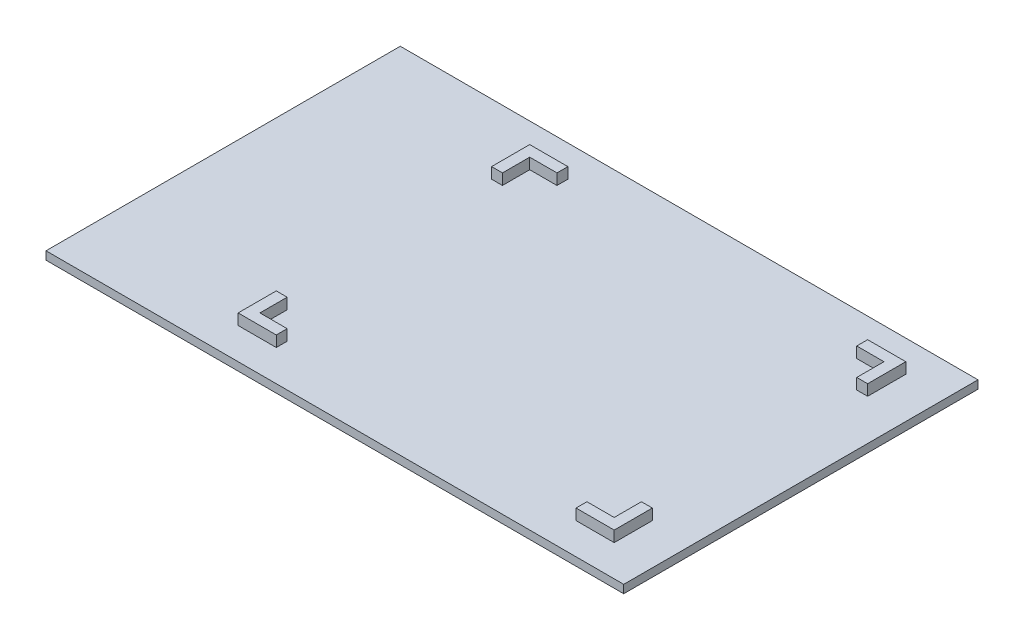
SolidWorks part; units mm, degrees
ref_plane "Front Plane" through (0, 0, 0) normal (0, 0, 1) x (1, 0, 0)
ref_plane "Top Plane" through (0, 0, 0) normal (0, 1, 0) x (1, 0, 0)
ref_plane "Right Plane" through (0, 0, 0) normal (1, 0, 0) x (0, 0, -1)
sketch "Sketch2" plane through (0, 0, 0) normal (0, 1, 0) x (1, 0, 0)
  line L0 (-106, 65) -> (-106, -65)
  line L1 (-106, -65) -> (106, -65)
  line L2 (106, -65) -> (106, 65)
  line L3 (106, 65) -> (-106, 65)
  point P2 (0, 65)
  point P5 (-106, 0)
  dimension "D1" = 212
  dimension "D2" = 130
extrude "Boss-Extrude1" add sketch "Sketch2" along normal blind 3
sketch "Sketch3" plane through (0, 3, 0) normal (0, 1, 0) x (1, 0, 0)
  line L0 (91, 53.5) -> (77, 53.5)
  line L1 (77, 53.5) -> (77, 49.5)
  line L2 (77, 49.5) -> (87, 49.5)
  line L3 (87, 49.5) -> (87, 39.5)
  line L4 (87, 39.5) -> (91, 39.5)
  line L5 (91, 39.5) -> (91, 53.5)
  line L6 (91, -39.5) -> (91, -53.5)
  line L7 (91, -53.5) -> (77, -53.5)
  line L8 (77, -53.5) -> (77, -49.5)
  line L9 (77, -49.5) -> (87, -49.5)
  line L10 (87, -49.5) -> (87, -39.5)
  line L11 (87, -39.5) -> (91, -39.5)
  line L12 (106, -65) -> (106, 65) construction
  line L13 (-106, -65) -> (106, -65) construction
  line L27 (22, 73.2387) -> (22, -80.6941) construction
  line L28 (-43, -49.5) -> (-43, -39.5)
  line L29 (-33, -49.5) -> (-43, -49.5)
  line L30 (-33, -53.5) -> (-33, -49.5)
  line L31 (-47, -53.5) -> (-33, -53.5)
  line L32 (-47, -39.5) -> (-47, -53.5)
  line L33 (-43, -39.5) -> (-47, -39.5)
  line L34 (-43, 39.5) -> (-47, 39.5)
  line L35 (-43, 49.5) -> (-43, 39.5)
  line L36 (-33, 49.5) -> (-43, 49.5)
  line L37 (-33, 53.5) -> (-33, 49.5)
  line L38 (-47, 53.5) -> (-33, 53.5)
  line L39 (-47, 39.5) -> (-47, 53.5)
  point P32 (0, 0)
  dimension "D1" = 4
  dimension "D2" = 4
  dimension "D3" = 10
  dimension "D4" = 10
  dimension "D5" = 4
  dimension "D6" = 14
  dimension "D7" = 4
  dimension "D8" = 14
  dimension "D9" = 99
  dimension "D10" = 15
  dimension "D11" = 11.5
  dimension "D12" = 65
extrude "Boss-Extrude2" add sketch "Sketch3" along normal blind 4
